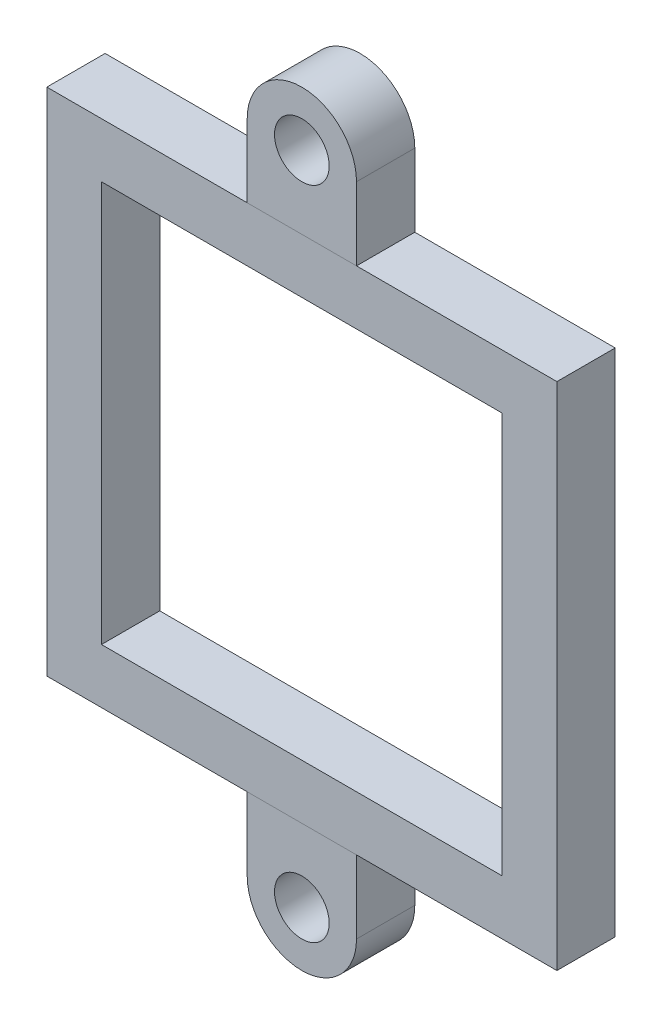
SolidWorks part; units mm, degrees
ref_plane "前视基准面" through (0, 0, 0) normal (0, 0, 1) x (1, 0, 0)
ref_plane "上视基准面" through (0, 0, 0) normal (0, 1, 0) x (1, 0, 0)
ref_plane "右视基准面" through (0, 0, 0) normal (1, 0, 0) x (0, 0, -1)
sketch "草图2" plane through (0, 0, 0) normal (0, 0, 1) x (1, 0, 0)
  line L5 (7, -7) -> (-7, -7)
  line L6 (7, -7) -> (7, 7)
  line L7 (7, 7) -> (-7, 7)
  line L8 (-7, -7) -> (-7, 7)
  line L9 (7, -7) -> (-7, 7) construction
  line L10 (7, 7) -> (-7, -7) construction
  point P0 (0, 0)
  dimension "D1" = 14
  dimension "D2" = 14
extrude "凸台-拉伸1" add sketch "草图2" along normal blind 1.6
sketch "草图3" plane through (0, -7, 0) normal (0, -1, 0) x (1, 0, 0)
  line L0 (7, 0) -> (-7, 0) construction
  line L1 (-1.5, 1.6) -> (1.5, 1.6)
  line L2 (-1.5, 1.6) -> (-1.5, 0)
  line L3 (-1.5, 0) -> (1.5, 0)
  line L4 (1.5, 1.6) -> (1.5, 0)
  line L5 (-1.5, 1.6) -> (1.5, 0) construction
  line L6 (-1.5, 0) -> (1.5, 1.6) construction
  line L7 (7, 1.6) -> (-7, 1.6) construction
  point P0 (0, 0.8)
  dimension "D1" = 3
extrude "凸台-拉伸2" add sketch "草图3" along normal blind 3.5 separate body
sketch "草图4" plane through (0, 0, 0) normal (0, 0, -1) x (-1, 0, 0)
  line L0 (1.5, -10.5) -> (1.5, -7) construction
  line L1 (1.5, -10.5) -> (-1.5, -10.5) construction
  line L2 (-1.5, -10.5) -> (-1.5, -7) construction
  line L3 (1.5, -9) -> (1.5, -10.5)
  line L4 (1.5, -10.5) -> (-1.5, -10.5)
  line L5 (-1.5, -10.5) -> (-1.5, -9)
  circle A0 centre (0, -9) radius 1.5
  line M3 (-1.5, -7) -> (-1.5, -10.5)
  line M4 (-1.5, -10.5) -> (1.5, -10.5)
  line M5 (1.5, -10.5) -> (1.5, -7)
extrude "切除-拉伸1" cut sketch "草图4" against normal blind 4 contours A0 L4 M5 | A0 M3 M4
sketch "草图5" plane through (0, 0, 0) normal (0, 0, -1) x (-1, 0, 0)
  circle A0 centre (0, -9) radius 0.75
  dimension "D1" = 1.5
  dimension "D2" = 9
extrude "切除-拉伸2" cut sketch "草图5" against normal blind 4
mirror "镜向7" about plane through (0, 0, 0) normal (0, 1, 0) of bodies 109
sketch "草图6" plane through (0, 0, 0) normal (0, 0, -1) x (-1, 0, 0)
  line L1 (-5.5, 5.5) -> (5.5, 5.5)
  line L2 (-5.5, 5.5) -> (-5.5, -5.5)
  line L3 (-5.5, -5.5) -> (5.5, -5.5)
  line L4 (5.5, 5.5) -> (5.5, -5.5)
  line L5 (-5.5, 5.5) -> (5.5, -5.5) construction
  line L6 (-5.5, -5.5) -> (5.5, 5.5) construction
  point P0 (0, 0)
  dimension "D1" = 11
  dimension "D2" = 11
extrude "切除-拉伸3" cut sketch "草图6" against normal blind 10 contours L4 L3 L2 L1
